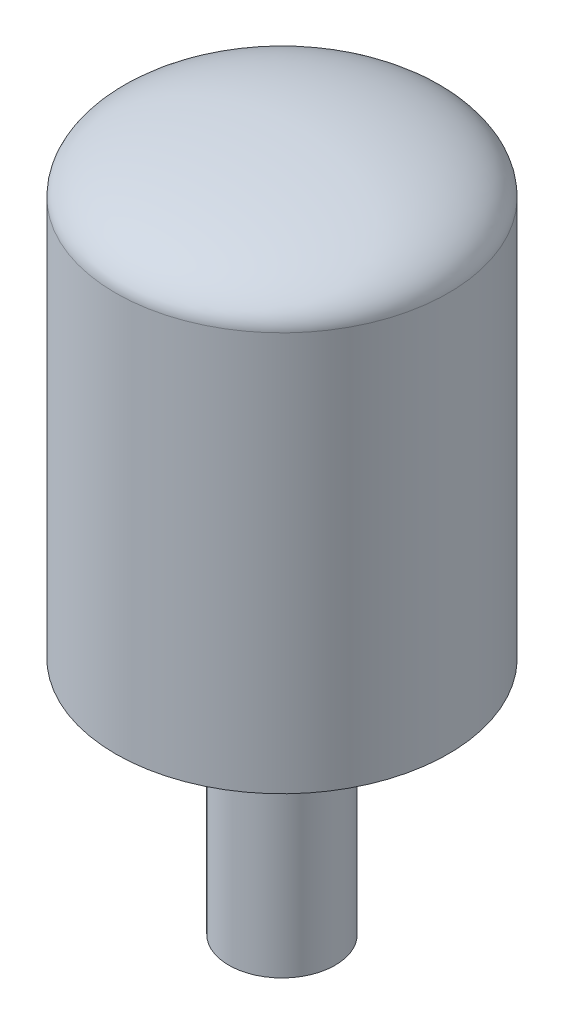
SolidWorks part; units mm, degrees
ref_plane "Front Plane" through (0, 0, 0) normal (0, 0, 1) x (1, 0, 0)
ref_plane "Top Plane" through (0, 0, 0) normal (0, 1, 0) x (1, 0, 0)
ref_plane "Right Plane" through (0, 0, 0) normal (1, 0, 0) x (0, 0, -1)
sketch "Sketch2" plane through (0, 0, 0) normal (1, 0, 0) x (0, 0, -1)
  line L0 (0, 0) -> (7.9375, 0)
  line L1 (55, 0) -> (-55, 0) construction
  line L2 (7.9375, 0) -> (7.9375, 19.05)
  line L4 (0, 55) -> (0, -55) construction
  line L5 (0, 21.7918) -> (0, 0)
  ellipse E0 centre (0, 19.05) end of major axis (7.9375, 19.05) minor radius 2.7418 (7.9375, 19.05) -> (0, 21.7918) ccw
  dimension "D1" = 7.9375
  dimension "D2" = 19.05
revolve "Revolve1" add sketch "Sketch2" angle 360 about L5
sketch "Sketch3" plane through (0, 0, 0) normal (0, -1, 0) x (1, 0, 0)
  circle A0 centre (0, 0) radius 2.54
  dimension "D1" = 5.08
extrude "Boss-Extrude1" add sketch "Sketch3" along normal blind 11.43
